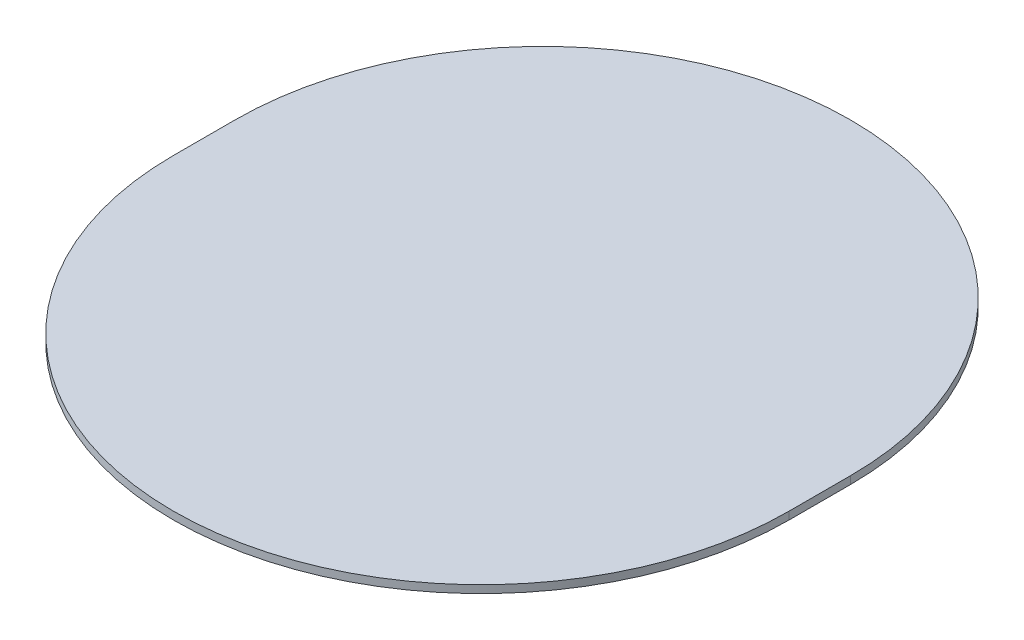
SolidWorks part; units mm, degrees
ref_plane "Front Plane" through (0, 0, 0) normal (0, 0, 1) x (1, 0, 0)
ref_plane "Top Plane" through (0, 0, 0) normal (0, 1, 0) x (1, 0, 0)
ref_plane "Right Plane" through (0, 0, 0) normal (1, 0, 0) x (0, 0, -1)
sketch "Sketch1" plane through (0, 0, 0) normal (0, 1, 0) x (1, 0, 0)
  line L1 (127, -12.7) -> (-127, -12.7) construction
  line L2 (127, -12.7) -> (127, 12.7)
  line L3 (127, 12.7) -> (-127, 12.7) construction
  line L4 (-127, -12.7) -> (-127, 12.7)
  line L5 (127, -12.7) -> (-127, 12.7) construction
  line L6 (127, 12.7) -> (-127, -12.7) construction
  arc A0 (-127, 12.7) -> (127, 12.7) centre (0, 12.7) cw
  arc A1 (-127, -12.7) -> (127, -12.7) centre (0, -12.7) ccw
  point P0 (0, 0)
  dimension "D1" = 254
  dimension "D2" = 25.4
extrude "Boss-Extrude1" add sketch "Sketch1" along normal blind 3.175
equation "\"thick\"=0.125"
equation "\"D1@Boss-Extrude1\"=\"thick\""
